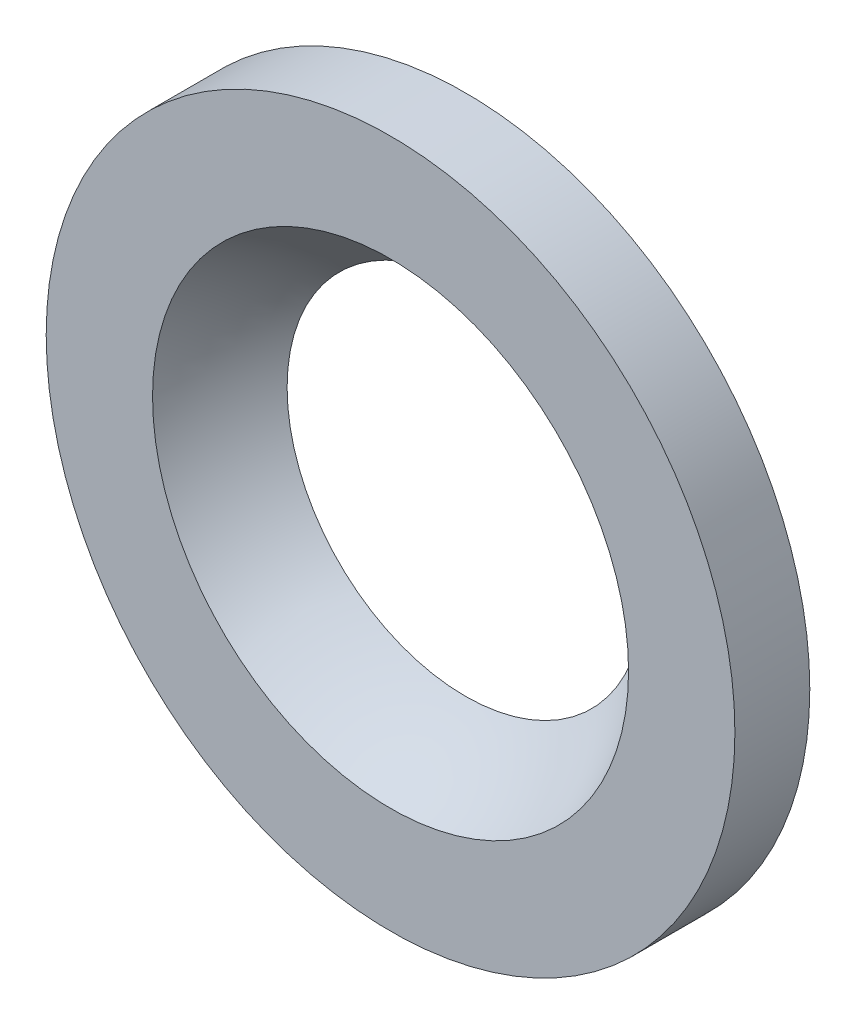
SolidWorks part; units mm, degrees
ref_plane "Front Plane" through (0, 0, 0) normal (0, 0, 1) x (1, 0, 0)
ref_plane "Top Plane" through (0, 0, 0) normal (0, 1, 0) x (1, 0, 0)
ref_plane "Right Plane" through (0, 0, 0) normal (1, 0, 0) x (0, 0, -1)
sketch "Sketch2" plane through (0, 0, 0) normal (0, 0, 1) x (1, 0, 0)
  circle A0 centre (0, 0) radius 32.1836
  dimension "D1" = 64.3671
extrude "Boss-Extrude1" add sketch "Sketch2" along normal blind 7
sketch "Sketch3" plane through (0, 0, 7) normal (0, 0, 1) x (1, 0, 0)
  circle A0 centre (0, 0) radius 10
  dimension "D1" = 20
extrude "Cut-Extrude1" cut sketch "Sketch3" against normal through all
sketch "Sketch4" plane through (0, 0, 0) normal (0, 1, 0) x (1, 0, 0)
  line L0 (0, 16.7642) -> (0, -16.7642) construction
  line L1 (-22.2449, -7) -> (0, -7)
  line L2 (-22.8388, 0) -> (22.8388, 0) construction
  line L5 (0, -7) -> (0, 4.2128)
  line L6 (0, 4.2128) -> (-10, 4.2128)
  arc A0 (-22.2449, -7) -> (-10, 4.2128) centre (0, -19) cw
  point P4 (0, 0)
  point P8 (0, 0)
  dimension "D1" = 25.2752
  dimension "D2" = 7
  dimension "D3" = 19
  dimension "D4" = 10
revolve "Cut-Revolve1" cut sketch "Sketch4" angle 360 about L0
